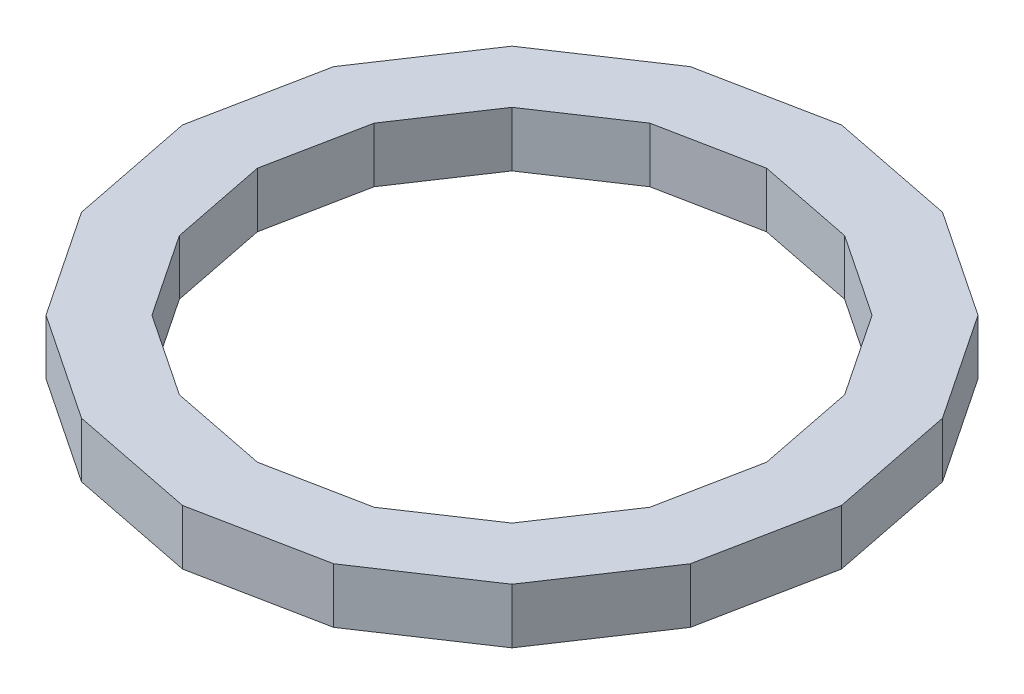
SolidWorks part; units mm, degrees
ref_plane "Front Plane" through (0, 0, 0) normal (0, 0, 1) x (1, 0, 0)
ref_plane "Top Plane" through (0, 0, 0) normal (0, 1, 0) x (1, 0, 0)
ref_plane "Right Plane" through (0, 0, 0) normal (1, 0, 0) x (0, 0, -1)
sketch "Sketch1" plane through (0, 0, 0) normal (0, 1, 0) x (1, 0, 0)
  line L1 (88.024, 0) -> (81.3236, 33.6853)
  line L2 (81.3236, 33.6853) -> (62.2424, 62.2424)
  line L3 (62.2424, 62.2424) -> (33.6853, 81.3236)
  line L4 (33.6853, 81.3236) -> (0, 88.024)
  line L5 (0, 88.024) -> (-33.6853, 81.3236)
  line L6 (-33.6853, 81.3236) -> (-62.2424, 62.2424)
  line L7 (-62.2424, 62.2424) -> (-81.3236, 33.6853)
  line L8 (-81.3236, 33.6853) -> (-88.024, 0)
  line L9 (-88.024, 0) -> (-81.3236, -33.6853)
  line L10 (-81.3236, -33.6853) -> (-62.2424, -62.2424)
  line L11 (-62.2424, -62.2424) -> (-33.6853, -81.3236)
  line L12 (-33.6853, -81.3236) -> (0, -88.024)
  line L13 (0, -88.024) -> (33.6853, -81.3236)
  line L14 (33.6853, -81.3236) -> (62.2424, -62.2424)
  line L15 (62.2424, -62.2424) -> (81.3236, -33.6853)
  line L16 (81.3236, -33.6853) -> (88.024, 0)
  line L17 (113.9216, 0) -> (105.2498, 43.5959)
  line L18 (105.2498, 43.5959) -> (80.5547, 80.5547)
  line L19 (80.5547, 80.5547) -> (43.5959, 105.2498)
  line L20 (43.5959, 105.2498) -> (0, 113.9216)
  line L21 (0, 113.9216) -> (-43.5959, 105.2498)
  line L22 (-43.5959, 105.2498) -> (-80.5547, 80.5547)
  line L23 (-80.5547, 80.5547) -> (-105.2498, 43.5959)
  line L24 (-105.2498, 43.5959) -> (-113.9216, 0)
  line L25 (-113.9216, 0) -> (-105.2498, -43.5959)
  line L26 (-105.2498, -43.5959) -> (-80.5547, -80.5547)
  line L27 (-80.5547, -80.5547) -> (-43.5959, -105.2498)
  line L28 (-43.5959, -105.2498) -> (0, -113.9216)
  line L29 (0, -113.9216) -> (43.5959, -105.2498)
  line L30 (43.5959, -105.2498) -> (80.5547, -80.5547)
  line L31 (80.5547, -80.5547) -> (105.2498, -43.5959)
  line L32 (105.2498, -43.5959) -> (113.9216, 0)
  circle A0 centre (0, 0) radius 86.3326 construction
  circle A1 centre (0, 0) radius 111.7326 construction
  dimension "D1" = 44.45
  dimension "D2" = 25.4
extrude "Boss-Extrude1" add sketch "Sketch1" along normal blind 19.05
